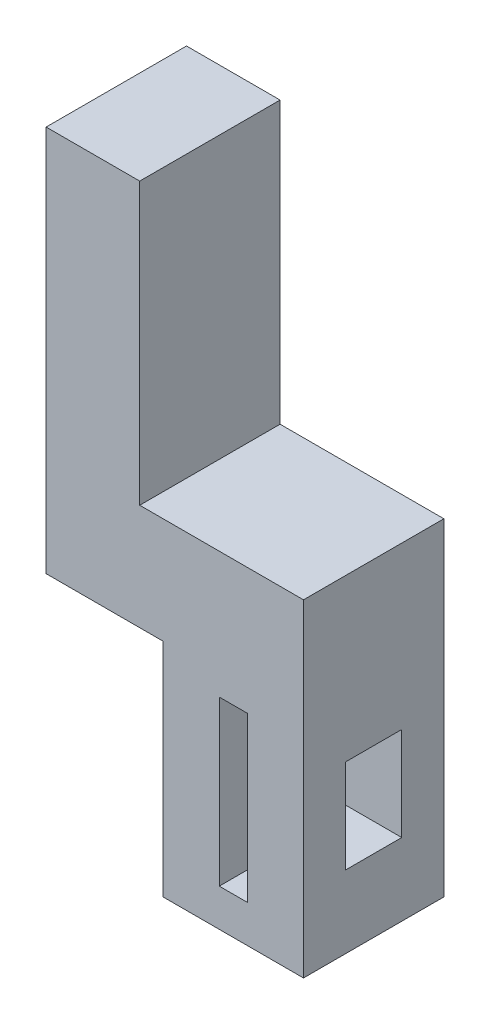
SolidWorks part; units mm, degrees
material "AISI 304"
ref_plane "Front Plane" through (0, 0, 0) normal (0, 0, 1) x (1, 0, 0)
ref_plane "Top Plane" through (0, 0, 0) normal (0, 1, 0) x (1, 0, 0)
ref_plane "Right Plane" through (0, 0, 0) normal (1, 0, 0) x (0, 0, -1)
sketch "Sketch1" plane through (0, 0, 0) normal (0, 1, 0) x (1, 0, 0)
  line L1 (0, 0) -> (30, 0)
  line L2 (0, 0) -> (0, -30)
  line L3 (0, -30) -> (30, -30)
  line L4 (30, 0) -> (30, -30)
  dimension "D1" = 30
  dimension "D2" = 30
extrude "Boss-Extrude1" add sketch "Sketch1" along normal blind 70
sketch "Sketch2" plane through (0, 0, 30) normal (0, 0, 1) x (1, 0, 0)
  line L0 (0, 0) -> (30, 0) construction
  line L1 (12, 43) -> (18, 43)
  line L2 (12, 43) -> (12, 8)
  line L3 (12, 8) -> (18, 8)
  line L4 (18, 43) -> (18, 8)
  point P6 (15, 8)
  point P7 (15, 0)
  dimension "D1" = 6
  dimension "D2" = 35
  dimension "D3" = 8
  dimension "D4" = 0
extrude "Cut-Extrude1" cut sketch "Sketch2" against normal through all
sketch "Sketch3" plane through (30, 0, 0) normal (1, 0, 0) x (0, 0, -1)
  line L0 (-30, 0) -> (0, 0) construction
  line L1 (-21, 35.5) -> (-9, 35.5)
  line L2 (-21, 35.5) -> (-21, 15.5)
  line L3 (-21, 15.5) -> (-9, 15.5)
  line L4 (-9, 35.5) -> (-9, 15.5)
  line L5 (0, 8) -> (-30, 8) construction
  point P4 (-15, 15.5)
  point P7 (-15, 0)
  dimension "D1" = 12
  dimension "D2" = 0
  dimension "D3" = 20
  dimension "D4" = 7.5
extrude "Cut-Extrude2" cut sketch "Sketch3" against normal through all
sketch "Sketch4" plane through (0, 0, 0) normal (-1, 0, 0) x (0, 0, 1)
  line L0 (30, 70) -> (30, 0) construction
  line L1 (0, 70) -> (30, 70)
  line L2 (0, 70) -> (0, 47.3304)
  line L3 (0, 47.3304) -> (30, 47.3304)
  line L4 (30, 70) -> (30, 47.3304)
extrude "Boss-Extrude2" add sketch "Sketch4" along normal blind 25
sketch "Sketch5" plane through (0, 70, 0) normal (0, 1, 0) x (1, 0, 0)
  line L0 (30, 0) -> (-25, 0) construction
  line L1 (-25, -30) -> (-5, -30)
  line L2 (-25, -30) -> (-25, 0)
  line L3 (-25, 0) -> (-5, 0)
  line L4 (-5, -30) -> (-5, 0)
  dimension "D1" = 20
extrude "Boss-Extrude3" add sketch "Sketch5" along normal blind 60
equation "\"D4@Sketch3\"=\"D2@Sketch2\"/2-\"D3@Sketch3\"/2"
